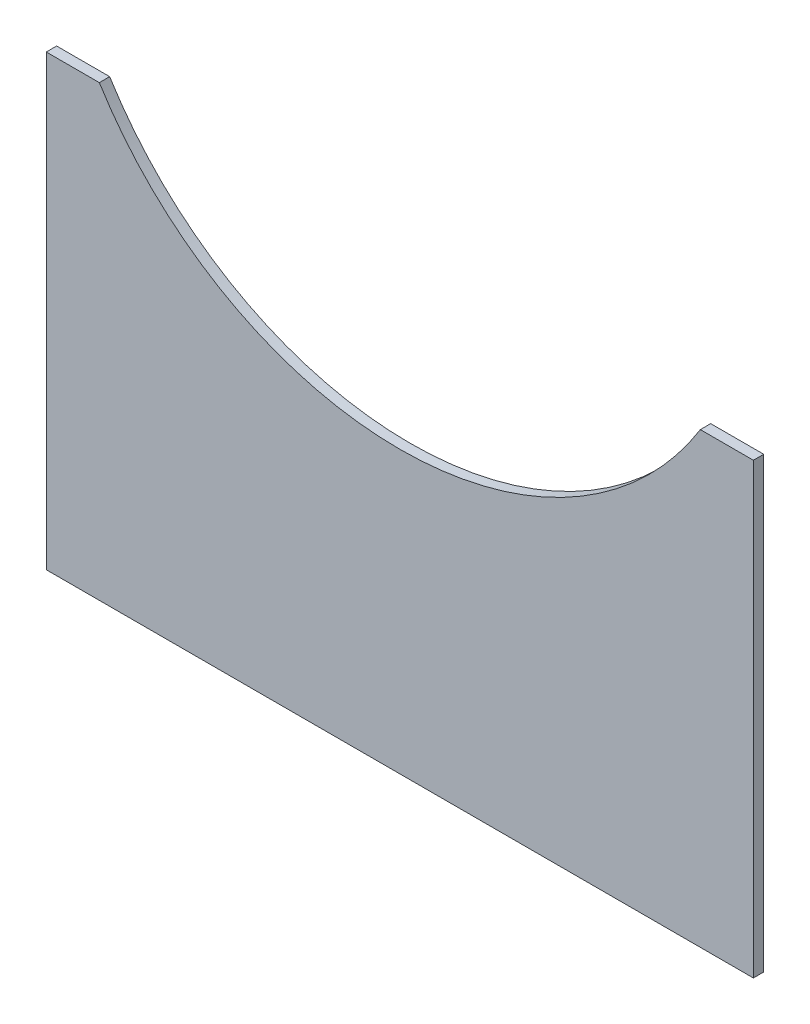
SolidWorks part; units mm, degrees
ref_plane "Front Plane" through (0, 0, 0) normal (0, 0, 1) x (1, 0, 0)
ref_plane "Top Plane" through (0, 0, 0) normal (0, 1, 0) x (1, 0, 0)
ref_plane "Right Plane" through (0, 0, 0) normal (1, 0, 0) x (0, 0, -1)
sketch "Sketch1" plane through (0, 0, 0) normal (0, 0, 1) x (1, 0, 0)
  line L0 (51.25, 0) -> (-51.25, 0)
  line L1 (-51.25, 0) -> (-51.25, 65)
  line L2 (-51.25, 65) -> (-43.561, 65)
  line L3 (0, 92) -> (0, 0) construction
  line L4 (51.25, 65) -> (43.561, 65)
  line L5 (51.25, 0) -> (51.25, 65)
  arc A2 (-43.561, 65) -> (43.561, 65) centre (0, 92) ccw
  point P5 (0, 71.875)
  point P11 (0, 85.9375)
  dimension "D3" = 102.5
  dimension "D1" = 102.5
  dimension "D2" = 65
  dimension "D4" = 92
extrude "Boss-Extrude1" add sketch "Sketch1" along normal mid plane 1.5
